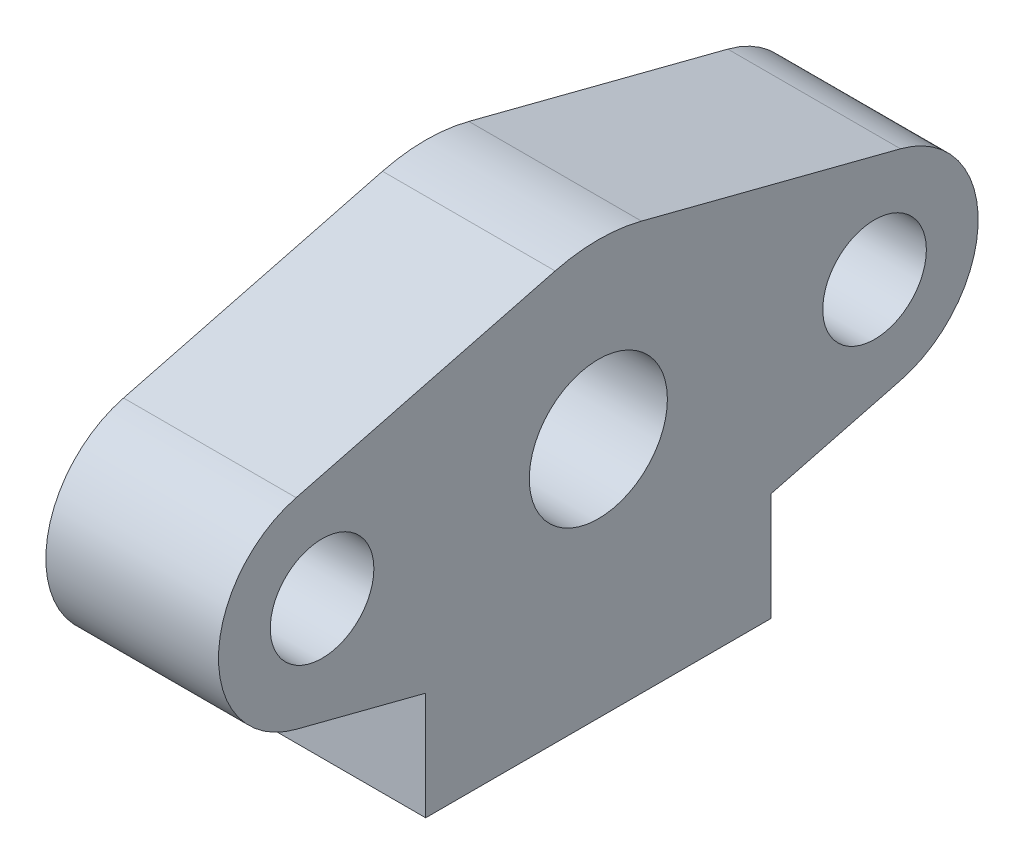
SolidWorks part; units mm, degrees
ref_plane "Front Plane" through (0, 0, 0) normal (0, 0, 1) x (1, 0, 0)
ref_plane "Top Plane" through (0, 0, 0) normal (0, 1, 0) x (1, 0, 0)
ref_plane "Right Plane" through (0, 0, 0) normal (1, 0, 0) x (0, 0, -1)
sketch "Sketch1" plane through (0, 0, 0) normal (1, 0, 0) x (0, 0, -1)
  line L2 (-16, 0) -> (0, 0) construction
  line L3 (0, 0) -> (16, 0) construction
  line L6 (0, 10) -> (0, -10) construction
  line L7 (-10, -7.746) -> (-10, -14)
  line L10 (-17.5, 5.8095) -> (-2.5, 9.6825)
  line L11 (-17.5, -5.8095) -> (-10, -7.746)
  line L12 (-10, -14) -> (10, -14)
  line L13 (17.5, 5.8095) -> (2.5, 9.6825)
  line L14 (17.5, -5.8095) -> (10, -7.746)
  line L15 (10, -7.746) -> (10, -14)
  circle A0 centre (0, 0) radius 4
  circle A1 centre (16, 0) radius 3
  circle A2 centre (-16, 0) radius 3
  arc A3 (-17.5, 5.8095) -> (-17.5, -5.8095) centre (-16, 0) ccw
  arc A6 (2.5, 9.6825) -> (-2.5, 9.6825) centre (0, 0) ccw
  arc A7 (17.5, 5.8095) -> (17.5, -5.8095) centre (16, 0) cw
  point P9 (0, 10)
  point P20 (0, -14)
  point P22 (0, -14)
  dimension "D1" = 8
  dimension "D2" = 6
  dimension "D3" = 6
  dimension "D6" = 3
  dimension "D4" = 16
  dimension "D5" = 24
  dimension "D8" = 10
  dimension "D9" = 10
extrude "Boss-Extrude1" add sketch "Sketch1" along normal blind 10
